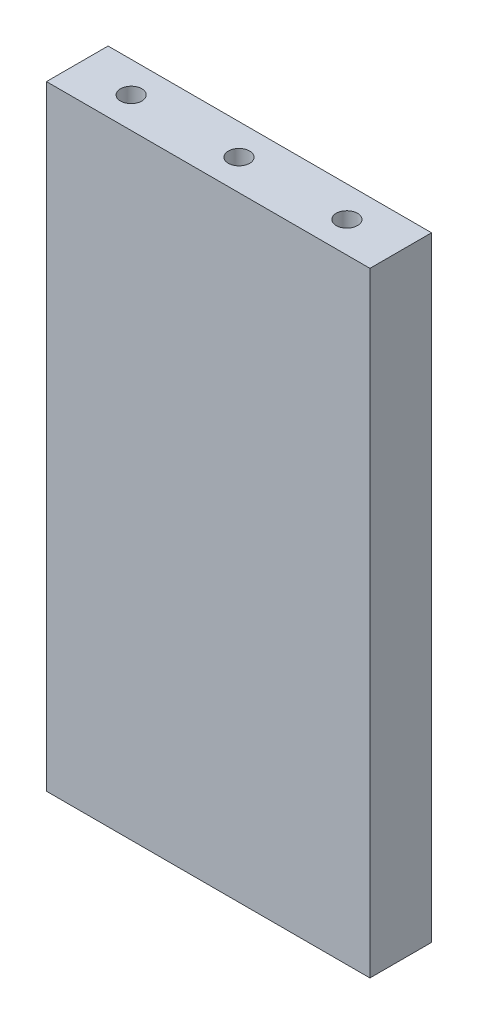
SolidWorks part; units mm, degrees
ref_plane "Front Plane" through (0, 0, 0) normal (0, 0, 1) x (1, 0, 0)
ref_plane "Top Plane" through (0, 0, 0) normal (0, 1, 0) x (1, 0, 0)
ref_plane "Right Plane" through (0, 0, 0) normal (1, 0, 0) x (0, 0, -1)
sketch "Sketch1" plane through (0, 0, 0) normal (0, 0, 1) x (1, 0, 0)
  line L1 (-25, -47.5) -> (25, -47.5)
  line L2 (-25, -47.5) -> (-25, 47.5)
  line L3 (-25, 47.5) -> (25, 47.5)
  line L4 (25, -47.5) -> (25, 47.5)
  line L5 (-25, -47.5) -> (25, 47.5) construction
  line L6 (-25, 47.5) -> (25, -47.5) construction
  point P0 (0, 0)
  dimension "D1" = 95
  dimension "D2" = 50
extrude "Boss-Extrude1" add sketch "Sketch1" against normal blind 9.525
sketch "Sketch2" plane through (0, 47.5, 0) normal (0, 1, 0) x (1, 0, 0)
  line L0 (25, 0) -> (-25, 0) construction
  point P0 (0, 4.7625)
  point P1 (16.67, 4.7625)
  point P2 (-16.67, 4.7625)
  dimension "D1" = 4.7625
  dimension "D2" = 16.67
  dimension "D3" = 16.67
sketch "Sketch3" plane through (0, -47.5, 0) normal (0, -1, 0) x (1, 0, 0)
  point P0 (16.67, -4.7625)
  point P2 (0, -4.7625)
  point P4 (-16.67, -4.7625)
hole_wizard "Tap Drill for M4x0.7 Tap1" positions "Sketch3" profile "Sketch4" hole size "M4x0.7" standard "ANSI Metric"
sketch "Sketch4" plane through (16.67, -47.5, -4.7625) normal (1, 0, 0) x (0, 0, -1)
  line L0 (0, 0) -> (0, 4.1914)
  line L1 (0, 4.1914) -> (1.65, 3.2)
  line L2 (1.65, 3.2) -> (1.65, 0)
  line L5 (1.65, 0) -> (0, 0)
  line L10 (0, 4.1914) -> (-1.65, 3.2) construction
  line L11 (0, -6.35) -> (0, 107.95) construction
  dimension "Hole Dia." = 3.3
  dimension "Hole Depth" = 3.2
  dimension "Drill Angle" = 118
hole_wizard "Tap Drill for M4x0.7 Tap2" positions "Sketch2" profile "Sketch5" hole size "M4x0.7" standard "ANSI Metric"
sketch "Sketch5" plane through (0, 47.5, -4.7625) normal (1, 0, 0) x (0, 0, 1)
  line L0 (0, 0) -> (0, 4.1914)
  line L1 (0, 4.1914) -> (1.65, 3.2)
  line L2 (1.65, 3.2) -> (1.65, 0)
  line L5 (1.65, 0) -> (0, 0)
  line L10 (0, 4.1914) -> (-1.65, 3.2) construction
  line L11 (0, -6.35) -> (0, 107.95) construction
  dimension "Hole Dia." = 3.3
  dimension "Hole Depth" = 3.2
  dimension "Drill Angle" = 118
